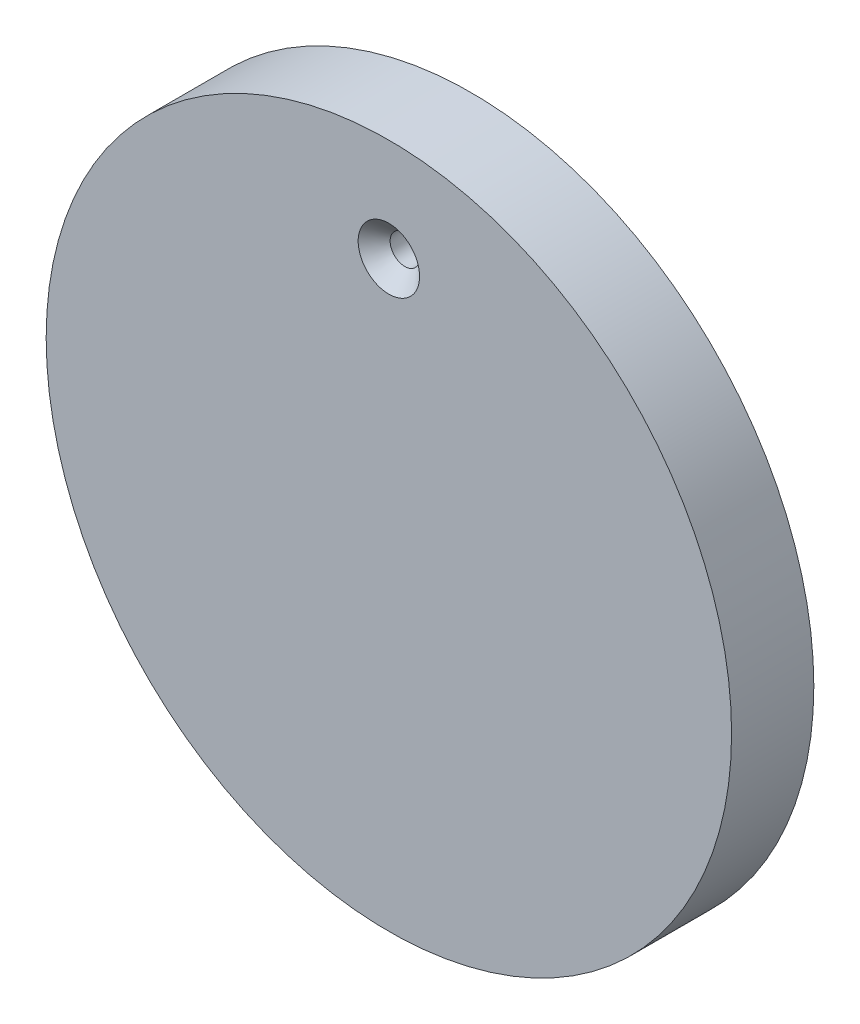
SolidWorks part; units mm, degrees
ref_plane "Front Plane" through (0, 0, 0) normal (0, 0, 1) x (1, 0, 0)
ref_plane "Top Plane" through (0, 0, 0) normal (0, 1, 0) x (1, 0, 0)
ref_plane "Right Plane" through (0, 0, 0) normal (1, 0, 0) x (0, 0, -1)
sketch "Sketch2" plane through (0, 0, 0) normal (0, 0, 1) x (1, 0, 0)
  circle A0 centre (0, 0) radius 50
  dimension "D1" = 100
extrude "Boss-Extrude1" add sketch "Sketch2" along normal blind 12
sketch "Sketch3" plane through (0, 0, 12) normal (0, 0, 1) x (1, 0, 0)
  line L0 (-50, 0) -> (50, 0) construction
  line L1 (0, 0) -> (0, 35) construction
  circle A0 centre (0, 0) radius 50 construction
  dimension "D1" = 35
hole_wizard "CSK for M4 SFHCS1" positions "3DSketch2" profile "Sketch5" countersink size "M4" standard "ANSI Metric"
sketch3d "3DSketch2"
  point P0 (0, 35, 12)
sketch "Sketch5" plane through (0, 35, 12) normal (1, 0, 0) x (0, -1, 0)
  line L0 (0, 0) -> (0, 20.7919)
  line L1 (0, 20.7919) -> (2.15, 19.5)
  line L2 (2.15, 19.5) -> (2.15, 2.33)
  line L3 (2.15, 2.33) -> (4.48, 0)
  line L5 (4.48, 0) -> (0, 0)
  line L6 (-2.15, 2.33) -> (-4.48, 0) construction
  line L10 (0, 20.7919) -> (-2.15, 19.5) construction
  line L11 (0, -6.35) -> (0, 107.95) construction
  dimension "Hole Dia." = 4.3
  dimension "Hole Depth" = 19.5
  dimension "Near C'Sink Dia." = 8.96
  dimension "Near C'Sink Angle" = 90
  dimension "Drill Angle" = 118
